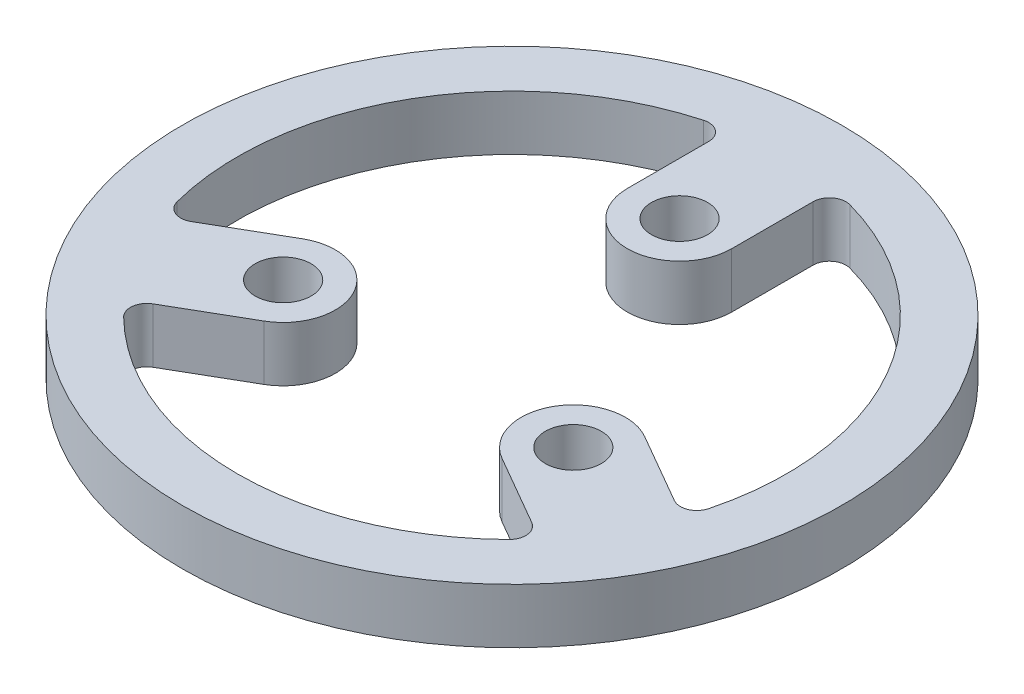
SolidWorks part; units mm, degrees
ref_plane "Front Plane" through (0, 0, 0) normal (0, 0, 1) x (1, 0, 0)
ref_plane "Top Plane" through (0, 0, 0) normal (0, 1, 0) x (1, 0, 0)
ref_plane "Right Plane" through (0, 0, 0) normal (1, 0, 0) x (0, 0, -1)
sketch "Sketch1" plane through (0, 0, 0) normal (0, 1, 0) x (1, 0, 0)
  circle A0 centre (0, 0) radius 30
  circle A4 centre (0, 0) radius 25
  dimension "D1" = 60
  dimension "D2" = 5
extrude "Boss-Extrude1" add sketch "Sketch1" along normal blind 5
sketch "Sketch2" plane through (0, 5, 0) normal (0, 1, 0) x (1, 0, 0)
  line L0 (-4.75, 15.25) -> (-4.75, 24.5446)
  line L1 (4.75, 15.25) -> (4.75, 24.5446)
  circle A0 centre (0, 0) radius 15.25 construction
  circle A1 centre (0, 15.25) radius 2.55
  arc A2 (-4.75, 15.25) -> (4.75, 15.25) centre (0, 15.25) ccw
  circle A3 centre (0, 0) radius 25 construction
  arc A4 (-4.75, 24.5446) -> (4.75, 24.5446) centre (0, 0) cw
  dimension "D1" = 30.5
  dimension "D2" = 5.1
  dimension "D3" = 2.2
extrude "Boss-Extrude2" add sketch "Sketch2" against normal up to surface (5 mm away) up to face at (0, 0, 30)
pattern_circular "CirPattern1" count 3 over 360 about axis through (0, 0, 0) along (0, 1, 0) of "Boss-Extrude2"
fillet "Fillet1" radius 1.5 6 edges at (23.6312, 2.5, 8.1587) (18.8812, 2.5, 16.3859) (-23.6312, 2.5, 8.1587) (-18.8812, 2.5, 16.3859) (4.75, 2.5, -24.5446) (-4.75, 2.5, -24.5446)
